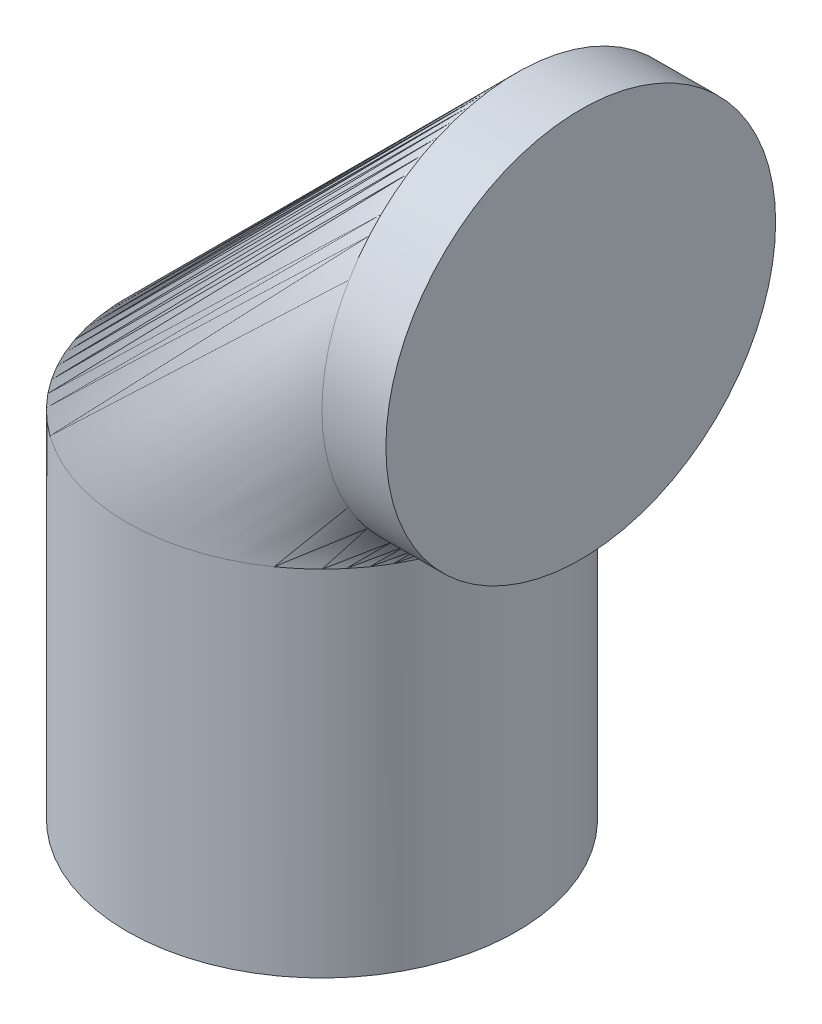
SolidWorks part; units mm, degrees
ref_plane "Front Plane" through (0, 0, 0) normal (0, 0, 1) x (1, 0, 0)
ref_plane "Top Plane" through (0, 0, 0) normal (0, 1, 0) x (1, 0, 0)
ref_plane "Right Plane" through (0, 0, 0) normal (1, 0, 0) x (0, 0, -1)
sketch "Sketch4" plane through (0, 0, 0) normal (0, 0, 1) x (1, 0, 0)
  line L0 (0, 0) -> (0, 45.42)
  line L1 (25, 70.42) -> (33.2, 70.42)
  arc A0 (0, 45.42) -> (25, 70.42) centre (25, 45.42) cw
  point P3 (0, 0)
  point P7 (0, 70.42)
  dimension "D3" = 25
  dimension "D1" = 70.42
  dimension "D2" = 33.2
sketch "Sketch5" plane through (0, 0, 0) normal (0, 1, 0) x (1, 0, 0)
  circle A0 centre (0, 0) radius 25
  dimension "D1" = 50
sweep "Sweep2" add profiles "Sketch5" path "Sketch4"
